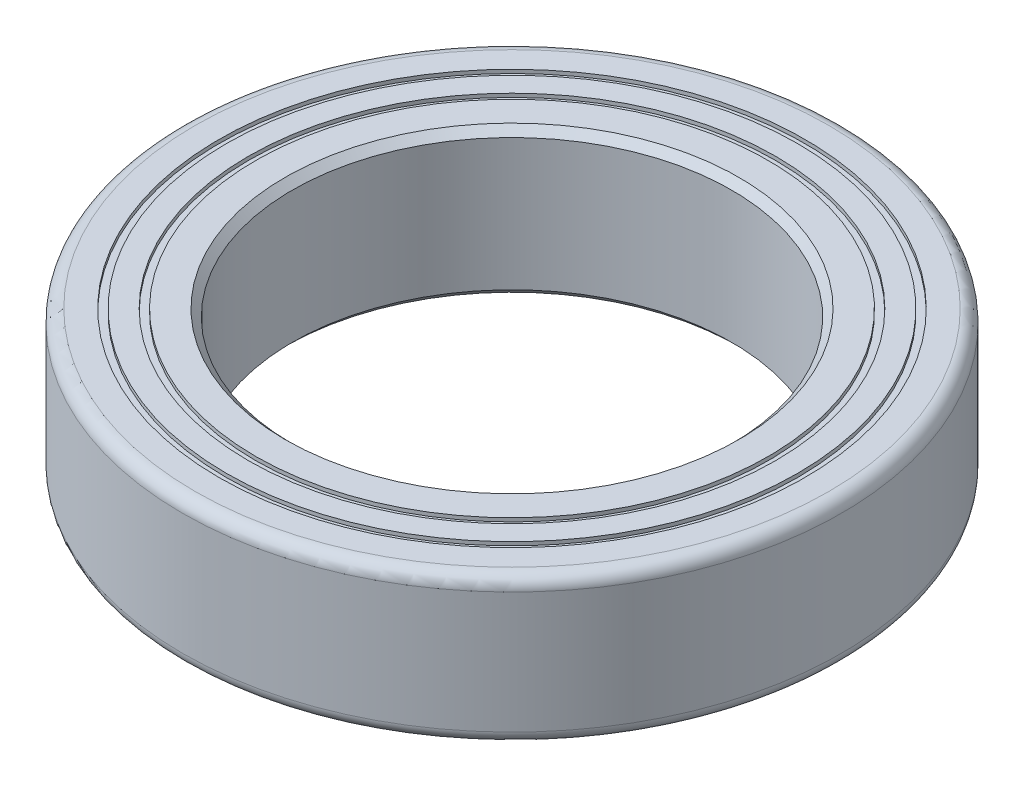
SolidWorks part; units mm, degrees
ref_plane "Front Plane" through (0, 0, 0) normal (0, 0, 1) x (1, 0, 0)
ref_plane "Top Plane" through (0, 0, 0) normal (0, 1, 0) x (1, 0, 0)
ref_plane "Right Plane" through (0, 0, 0) normal (1, 0, 0) x (0, 0, -1)
sketch "Sketch1" plane through (0, 0, 0) normal (0, 0, 1) x (1, 0, 0)
  line L0 (0, 0) -> (6, 0) construction
  line L1 (9, 0) -> (9, 4)
  line L3 (0, 2) -> (0, 0) construction
  line L4 (6, 0) -> (6, 4)
  line L5 (6, 0) -> (7, 0)
  line L6 (7, 0) -> (7, 0.1)
  line L7 (7, 0.1) -> (7.2, 0.1)
  line L8 (7.2, 0.1) -> (7.2, 0)
  line L9 (7.2, 0) -> (7.8, 0)
  line L10 (7.5, 0) -> (7.5, 2) construction
  line L11 (9, 2) -> (6, 2) construction
  line L12 (6, 2) -> (0, 2) construction
  line L13 (7.8, 0.1) -> (7.8, 0)
  line L14 (8, 0.1) -> (7.8, 0.1)
  line L15 (8, 0) -> (8, 0.1)
  line L16 (9, 0) -> (8, 0)
  line L17 (9, 4) -> (8, 4)
  line L18 (8, 4) -> (8, 3.9)
  line L19 (8, 3.9) -> (7.8, 3.9)
  line L20 (7.8, 3.9) -> (7.8, 4)
  line L21 (7.2, 4) -> (7.8, 4)
  line L22 (7.2, 3.9) -> (7.2, 4)
  line L23 (7, 3.9) -> (7.2, 3.9)
  line L24 (7, 4) -> (7, 3.9)
  line L25 (6, 4) -> (7, 4)
  dimension "D1" = 9
  dimension "D2" = 6
  dimension "D4" = 1
  dimension "D5" = 0.2
  dimension "D6" = 0.1
  dimension "D3" = 4
revolve "Revolve1" add sketch "Sketch1" angle 360 about L3
fillet "Fillet2" radius 0.344 2 edges at (0, 0, 9) (0, 4, 9)
chamfer "Chamfer2" distance 0.2 angle 45 2 edges at (0, 0, 6) (0, 4, 6)
equation "\"Ratio\"= 15"
equation "\"Hull Diameter\"= 92"
equation "\"Fixed Ring Diameter\"= 76"
equation "\"Fixed Pin Diameter\"= 6"
equation "\"Output Ring Diameter\"= 40"
equation "\"Output Pin Diameter\"= 6"
equation "\"Disk Bearing Inner Diameter\"= 9"
equation "\"Disk Bearing Outer Diameter\"= 17"
equation "\"Disk Bearing Height\"= 5"
equation "\"Shaft Bearing Inner Diameter\"= 15"
equation "\"Shaft Bearing Outer Diameter\"= 21"
equation "\"Shaft Bearing Height\"= 4"
equation "\"Eccentricity\"= 1.5"
equation "\"Disk Height\"= 8"
equation "\"Disk Spacing\"= 5"
equation "\"Hull Height\"= 40"
equation "\"Shaft End Bearing Inner Diameter\"= 12"
equation "\"Shaft End Bearing Outer Diameter\"= 18"
equation "\"Shaft End Bearing Height\"= 4"
equation "\"Output Bearing Inner Diameter\"= 55"
equation "\"Output Bearing Outer Diameter\"= 72"
equation "\"Outer Bearing Height\"= 9"
equation "\"D3@Sketch1\"=\"Shaft End Bearing Height\""
equation "\"D2@Sketch1\"=\"Shaft End Bearing Inner Diameter\"/2"
equation "\"D1@Sketch1\"=\"Shaft End Bearing Outer Diameter\"/2"
